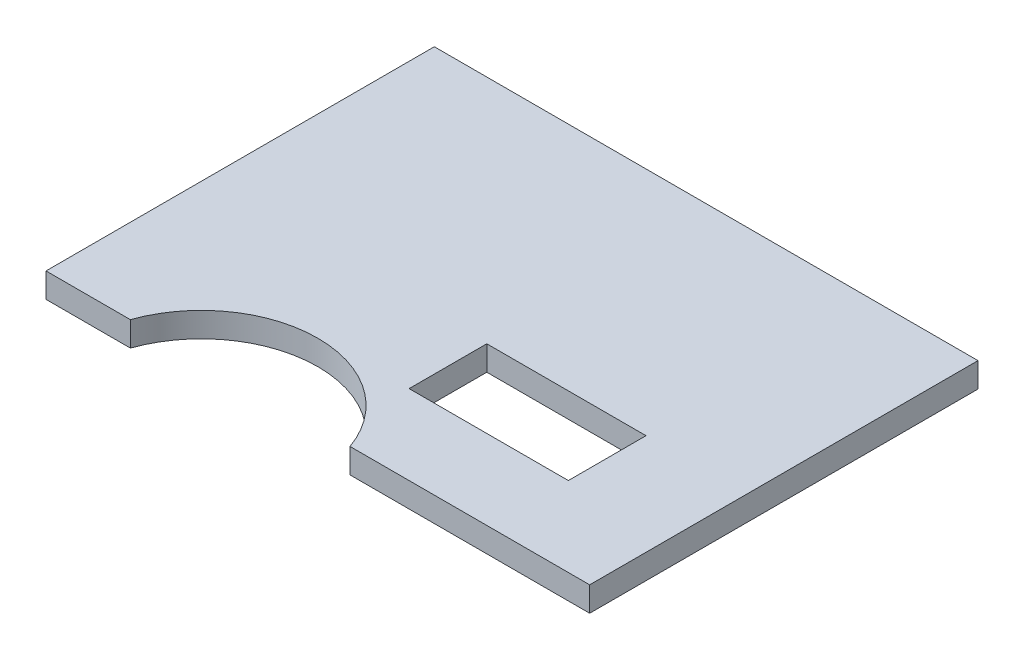
SolidWorks part; units mm, degrees
material "Oak"
ref_plane "Front Plane" through (0, 0, 0) normal (0, 0, 1) x (1, 0, 0)
ref_plane "Top Plane" through (0, 0, 0) normal (0, 1, 0) x (1, 0, 0)
ref_plane "Right Plane" through (0, 0, 0) normal (1, 0, 0) x (0, 0, -1)
sketch "Sketch1" plane through (0, 0, 0) normal (0, 1, 0) x (1, 0, 0)
  line L1 (0, 0) -> (140, 0)
  line L2 (0, 0) -> (0, 100)
  line L3 (0, 100) -> (140, 100)
  line L4 (140, 0) -> (140, 100)
  dimension "D1" = 140
  dimension "D2" = 100
extrude "Boss-Extrude1" add sketch "Sketch1" along normal blind 6.35
sketch "Sketch2" plane through (0, 6.35, 0) normal (0, 1, 0) x (1, 0, 0)
  line L0 (140, 0) -> (140, 100) construction
  line L1 (0, 0) -> (140, 0) construction
  line L3 (73, 40.51) -> (114, 40.51)
  line L4 (73, 40.51) -> (73, 20.51)
  line L5 (73, 20.51) -> (114, 20.51)
  line L6 (114, 40.51) -> (114, 20.51)
  point P0 (103.75, 30.51)
  dimension "D1" = 36.25
  dimension "D2" = 30.51
  dimension "D3" = 41
  dimension "D4" = 20
  dimension "D5" = 10
  dimension "D6" = 30.75
extrude "Cut-Extrude1" cut sketch "Sketch2" against normal blind 10
sketch "Sketch3" plane through (0, 6.35, 0) normal (0, 1, 0) x (1, 0, 0)
  line L0 (0, 0) -> (140, 0) construction
  line L1 (0, 100) -> (0, 0) construction
  circle A0 centre (50, -10) radius 30
  dimension "D1" = 60
  dimension "D2" = 10
  dimension "D3" = 50
extrude "Cut-Extrude2" cut sketch "Sketch3" against normal blind 10
